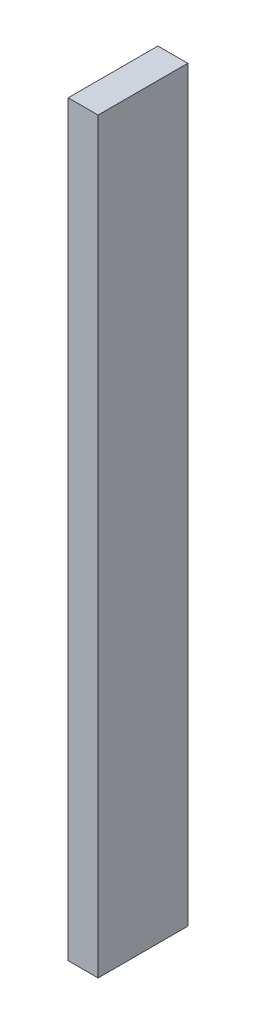
SolidWorks part; units mm, degrees
ref_plane "Front Plane" through (0, 0, 0) normal (0, 0, 1) x (1, 0, 0)
ref_plane "Top Plane" through (0, 0, 0) normal (0, 1, 0) x (1, 0, 0)
ref_plane "Right Plane" through (0, 0, 0) normal (1, 0, 0) x (0, 0, -1)
sketch "Sketch1" plane through (0, 0, 0) normal (0, 1, 0) x (1, 0, 0)
  line L1 (-10, -30) -> (10, -30)
  line L2 (-10, -30) -> (-10, 30)
  line L3 (-10, 30) -> (10, 30)
  line L4 (10, -30) -> (10, 30)
  line L5 (-10, -30) -> (10, 30) construction
  line L6 (-10, 30) -> (10, -30) construction
  point P0 (0, 0)
  dimension "D1" = 60
  dimension "D2" = 20
extrude "Boss-Extrude1" add sketch "Sketch1" along normal blind 500
